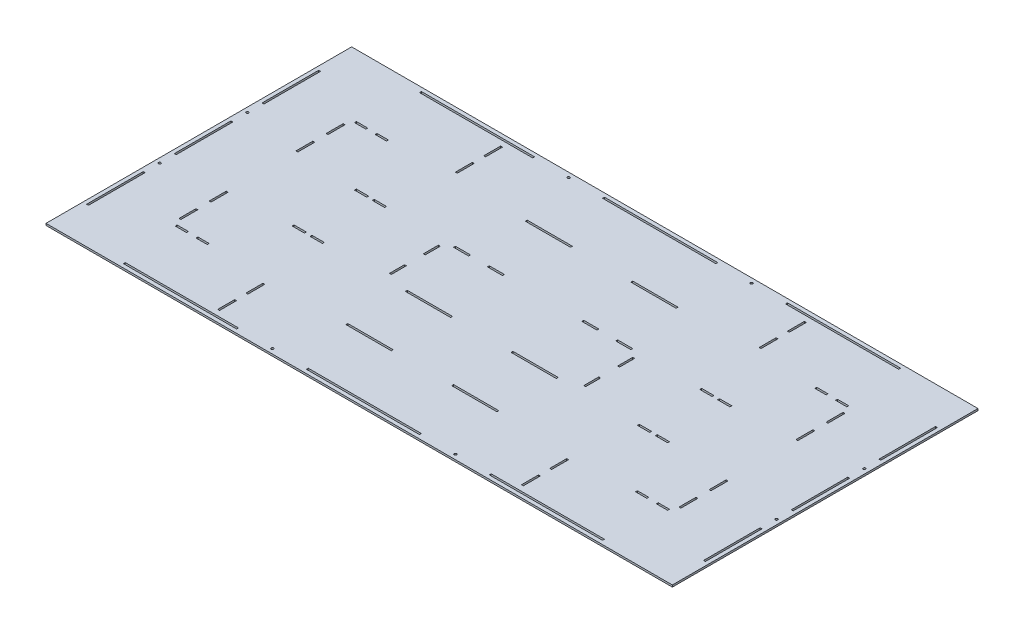
SolidWorks part; units mm, degrees
ref_plane "Alzado" through (0, 0, 0) normal (0, 0, 1) x (1, 0, 0)
ref_plane "Planta" through (0, 0, 0) normal (0, 1, 0) x (1, 0, 0)
ref_plane "Vista lateral" through (0, 0, 0) normal (1, 0, 0) x (0, 0, -1)
sketch "Croquis1" plane through (0, 0, 0) normal (0, 1, 0) x (1, 0, 0)
  line L4 (-447.0447, -95.6027) -> (-447.0447, -240.6027)
  line L5 (-2097.0447, -803.1027) -> (-437.0447, -803.1027)
  line L6 (-437.0447, 6.8973) -> (-437.0447, -803.1027)
  line L7 (-2097.0447, 6.8973) -> (-437.0447, 6.8973)
  line L13 (-2097.0447, 6.8973) -> (-2097.0447, -803.1027)
  line L18 (-2087.0447, -793.1027) -> (-447.0447, -793.1027) construction
  line L19 (-932.0447, -3.1027) -> (-632.0447, -3.1027)
  line L25 (-2097.0447, 6.8973) -> (-2097.0447, -803.1027) construction
  line L29 (-1117.0447, -3.1027) -> (-1417.0447, -3.1027)
  line L30 (-1117.0447, -8.1027) -> (-1117.0447, -3.1027)
  line L32 (-1417.0447, -3.1027) -> (-1417.0447, -8.1027)
  line L33 (-1602.0447, -8.1027) -> (-1902.0447, -8.1027)
  line L34 (-1902.0447, -3.1027) -> (-1602.0447, -3.1027)
  line L35 (-1902.0447, -3.1027) -> (-1902.0447, -8.1027)
  line L36 (-1602.0447, -3.1027) -> (-1602.0447, -8.1027)
  line L37 (-2097.0447, 6.8973) -> (-437.0447, 6.8973)
  line L38 (-632.0447, -3.1027) -> (-632.0447, -8.1027)
  line L39 (-2087.0447, -3.1027) -> (-447.0447, -3.1027) construction
  line L40 (-932.0447, -3.1027) -> (-932.0447, -8.1027)
  line L41 (-452.0447, -95.6027) -> (-452.0447, -90.6027)
  line L42 (-447.0447, -3.1027) -> (-447.0447, -793.1027) construction
  line L45 (-452.0447, -95.6027) -> (-452.0447, -240.6027)
  line L49 (-452.0447, -328.1027) -> (-452.0447, -473.1027)
  line L51 (-447.0447, -328.1027) -> (-447.0447, -473.1027)
  line L53 (-452.0447, -560.6027) -> (-452.0447, -705.6027)
  line L55 (-447.0447, -560.6027) -> (-447.0447, -705.6027)
  line L67 (-2087.0447, -3.1027) -> (-2087.0447, -793.1027) construction
  line L68 (-447.0447, -95.6027) -> (-447.0447, -90.6027)
  line L69 (-447.0447, -90.6027) -> (-452.0447, -90.6027)
  line L70 (-447.0447, -328.1027) -> (-447.0447, -323.1027)
  line L71 (-447.0447, -240.6027) -> (-452.0447, -240.6027) construction
  line L72 (-447.0447, -240.6027) -> (-452.0447, -240.6027)
  line L73 (-452.0447, -328.1027) -> (-452.0447, -323.1027)
  line L74 (-452.0447, -323.1027) -> (-447.0447, -323.1027)
  line L75 (-447.0447, -473.1027) -> (-452.0447, -473.1027)
  line L76 (-452.0447, -560.6027) -> (-452.0447, -555.6027)
  line L77 (-447.0447, -560.6027) -> (-447.0447, -555.6027)
  line L78 (-447.0447, -555.6027) -> (-452.0447, -555.6027)
  line L79 (-632.0447, -8.1027) -> (-932.0447, -8.1027)
  line L80 (-447.0447, -705.6027) -> (-452.0447, -705.6027)
  line L81 (-2087.0447, -240.6027) -> (-2082.0447, -240.6027) construction
  line L82 (-2087.0447, -705.6027) -> (-2082.0447, -705.6027)
  line L83 (-2087.0447, -555.6027) -> (-2082.0447, -555.6027)
  line L84 (-2087.0447, -560.6027) -> (-2087.0447, -555.6027)
  line L85 (-2082.0447, -560.6027) -> (-2082.0447, -555.6027)
  line L86 (-2087.0447, -473.1027) -> (-2082.0447, -473.1027)
  line L87 (-2082.0447, -323.1027) -> (-2087.0447, -323.1027)
  line L88 (-2082.0447, -328.1027) -> (-2082.0447, -323.1027)
  line L89 (-2087.0447, -240.6027) -> (-2082.0447, -240.6027)
  line L90 (-2087.0447, -328.1027) -> (-2087.0447, -323.1027)
  line L91 (-2087.0447, -90.6027) -> (-2082.0447, -90.6027)
  line L92 (-2087.0447, -95.6027) -> (-2087.0447, -90.6027)
  line L93 (-2087.0447, -560.6027) -> (-2087.0447, -705.6027)
  line L94 (-2082.0447, -560.6027) -> (-2082.0447, -705.6027)
  line L95 (-2087.0447, -328.1027) -> (-2087.0447, -473.1027)
  line L96 (-2082.0447, -328.1027) -> (-2082.0447, -473.1027)
  line L97 (-2082.0447, -95.6027) -> (-2082.0447, -240.6027)
  line L98 (-2082.0447, -95.6027) -> (-2082.0447, -90.6027)
  line L99 (-2087.0447, -95.6027) -> (-2087.0447, -240.6027)
  line L100 (-1117.0447, -8.1027) -> (-1417.0447, -8.1027)
  line L101 (-1117.0447, -788.1027) -> (-1417.0447, -788.1027)
  line L102 (-632.0447, -788.1027) -> (-932.0447, -788.1027)
  line L103 (-932.0447, -793.1027) -> (-932.0447, -788.1027)
  line L104 (-632.0447, -793.1027) -> (-632.0447, -788.1027)
  line L105 (-1602.0447, -793.1027) -> (-1602.0447, -788.1027)
  line L106 (-1902.0447, -793.1027) -> (-1902.0447, -788.1027)
  line L107 (-1902.0447, -793.1027) -> (-1602.0447, -793.1027)
  line L108 (-1602.0447, -788.1027) -> (-1902.0447, -788.1027)
  line L109 (-1417.0447, -793.1027) -> (-1417.0447, -788.1027)
  line L110 (-1117.0447, -788.1027) -> (-1117.0447, -793.1027)
  line L111 (-1117.0447, -793.1027) -> (-1417.0447, -793.1027)
  line L112 (-932.0447, -793.1027) -> (-632.0447, -793.1027)
  dimension "D5" = 5
  dimension "D10" = 145
  dimension "D3" = 1660
  dimension "D12" = 5
  dimension "D13" = 145
  dimension "D14" = 5
  dimension "D15" = 5
extrude "Saliente-Extruir3" add sketch "Croquis1" along normal blind 5 contours L7 L13 L5 L6 L112 L103 L102 L104 L108 L105 L107 L106 L99 L92 L91 L98 L97 L89 L34 L36 L33 L35 L4 L72 L45 L41 L69 L68 L51 L75 L49 L73 L74 L70 L38 L79 L40 L19 L55 L80 L53 L76 L78
sketch "Croquis2" plane through (0, 5, 0) normal (0, 1, 0) x (1, 0, 0)
  line L0 (-1007.0447, -463.1027) -> (-1007.0447, -423.1027)
  line L1 (-669.5447, -638.1027) -> (-699.5447, -638.1027)
  line L2 (-1067.0447, -638.1027) -> (-1187.0447, -638.1027)
  line L5 (-1467.0447, -633.1027) -> (-1347.0447, -633.1027)
  line L8 (-1602.0447, -788.1027) -> (-1902.0447, -788.1027) construction
  line L11 (-1672.0447, -788.1027) -> (-1667.0447, -788.1027)
  line L19 (-644.5447, -633.1027) -> (-644.5447, -638.1027)
  line L24 (-1464.5447, -483.1027) -> (-1344.5447, -483.1027)
  line L25 (-669.5447, -638.1027) -> (-669.5447, -633.1027)
  line L26 (-1672.0447, -8.1027) -> (-1667.0447, -8.1027)
  line L61 (-769.5447, -478.1027) -> (-802.0447, -478.1027)
  line L63 (-849.5447, -483.1027) -> (-817.0447, -483.1027)
  line L65 (-602.0447, -490.6027) -> (-602.0447, -535.6027)
  line L68 (-699.5447, -633.1027) -> (-669.5447, -633.1027)
  line L70 (-862.0447, -653.1027) -> (-862.0447, -698.1027)
  line L72 (-867.0447, -653.1027) -> (-867.0447, -698.1027)
  line L74 (-1032.0447, -313.1027) -> (-1072.0447, -313.1027)
  line L76 (-1162.0447, -318.1027) -> (-1122.0447, -318.1027)
  line L77 (-1012.0447, -333.1027) -> (-1012.0447, -373.1027)
  line L78 (-1064.5447, -478.1027) -> (-1184.5447, -478.1027)
  line L80 (-1122.0447, -313.1027) -> (-1122.0447, -318.1027)
  line L87 (-699.5447, -633.1027) -> (-699.5447, -638.1027)
  line L88 (-614.5447, -638.1027) -> (-644.5447, -638.1027)
  line L89 (-614.5447, -638.1027) -> (-614.5447, -633.1027)
  line L90 (-607.0447, -615.6027) -> (-602.0447, -615.6027)
  line L91 (-607.0447, -570.6027) -> (-602.0447, -570.6027)
  line L92 (-602.0447, -570.6027) -> (-602.0447, -615.6027)
  line L93 (-607.0447, -490.6027) -> (-607.0447, -535.6027)
  line L94 (-1187.0447, -158.1027) -> (-1187.0447, -163.1027)
  line L95 (-607.0447, -535.6027) -> (-602.0447, -535.6027)
  line L96 (-607.0447, -615.6027) -> (-607.0447, -570.6027)
  line L97 (-802.0447, -478.1027) -> (-802.0447, -483.1027)
  line L99 (-604.5447, -535.6027) -> (-602.0447, -535.6027) construction
  line L100 (-817.0447, -483.1027) -> (-817.0447, -478.1027)
  line L101 (-644.5447, -633.1027) -> (-614.5447, -633.1027)
  line L102 (-1467.0447, -158.1027) -> (-1467.0447, -163.1027)
  line L103 (-867.0447, -653.1027) -> (-862.0447, -653.1027)
  line L104 (-867.0447, -698.1027) -> (-862.0447, -698.1027)
  line L105 (-862.0447, -728.1027) -> (-867.0447, -728.1027)
  line L106 (-862.0447, -728.1027) -> (-862.0447, -773.1027)
  line L107 (-867.0447, -728.1027) -> (-867.0447, -773.1027)
  line L108 (-867.0447, -773.1027) -> (-862.0447, -773.1027)
  line L109 (-1347.0447, -638.1027) -> (-1467.0447, -638.1027)
  line L110 (-849.5447, -478.1027) -> (-849.5447, -483.1027)
  line L111 (-769.5447, -483.1027) -> (-769.5447, -478.1027)
  line L112 (-802.0447, -483.1027) -> (-769.5447, -483.1027)
  line L113 (-817.0447, -478.1027) -> (-849.5447, -478.1027)
  line L114 (-1267.0447, -8.1027) -> (-1267.0447, -98.1027)
  line L115 (-1064.5447, -478.1027) -> (-1064.5447, -483.1027)
  line L116 (-1184.5447, -478.1027) -> (-1184.5447, -483.1027)
  line L117 (-1464.5447, -478.1027) -> (-1464.5447, -483.1027)
  line L118 (-1344.5447, -478.1027) -> (-1344.5447, -483.1027)
  line L121 (-1184.5447, -483.1027) -> (-1064.5447, -483.1027)
  line L122 (-1344.5447, -478.1027) -> (-1464.5447, -478.1027)
  line L123 (-1117.0447, -8.1027) -> (-1417.0447, -8.1027) construction
  line L124 (-1412.0447, -313.1027) -> (-1412.0447, -318.1027) construction
  line L126 (-1067.0447, -633.1027) -> (-1067.0447, -638.1027)
  line L127 (-1187.0447, -638.1027) -> (-1187.0447, -633.1027)
  line L128 (-1347.0447, -638.1027) -> (-1347.0447, -633.1027)
  line L129 (-1467.0447, -633.1027) -> (-1467.0447, -638.1027)
  line L130 (-1187.0447, -633.1027) -> (-1067.0447, -633.1027)
  line L131 (-1412.0447, -313.1027) -> (-1372.0447, -313.1027)
  line L132 (-1927.0447, -305.6027) -> (-1932.0447, -305.6027)
  line L133 (-1462.0447, -318.1027) -> (-1502.0447, -318.1027)
  line L134 (-1012.0447, -423.1027) -> (-1012.0447, -463.1027)
  line L136 (-1012.0447, -463.1027) -> (-1007.0447, -463.1027)
  line L137 (-1012.0447, -423.1027) -> (-1007.0447, -423.1027)
  line L138 (-1012.0447, -373.1027) -> (-1007.0447, -373.1027)
  line L139 (-1007.0447, -333.1027) -> (-1012.0447, -333.1027)
  line L140 (-1007.0447, -373.1027) -> (-1007.0447, -333.1027)
  line L141 (-1032.0447, -313.1027) -> (-1032.0447, -318.1027)
  line L142 (-1072.0447, -313.1027) -> (-1072.0447, -318.1027)
  line L143 (-1372.0447, -313.1027) -> (-1372.0447, -318.1027)
  line L144 (-1162.0447, -313.1027) -> (-1162.0447, -318.1027)
  line L145 (-1122.0447, -313.1027) -> (-1122.0447, -318.1027) construction
  line L146 (-1072.0447, -318.1027) -> (-1032.0447, -318.1027)
  line L147 (-1122.0447, -313.1027) -> (-1162.0447, -313.1027)
  line L148 (-1929.5447, -535.6027) -> (-1932.0447, -535.6027) construction
  line L149 (-1717.0447, -478.1027) -> (-1684.5447, -478.1027)
  line L150 (-1732.0447, -483.1027) -> (-1764.5447, -483.1027)
  line L151 (-1764.5447, -483.1027) -> (-1764.5447, -478.1027)
  line L152 (-1684.5447, -478.1027) -> (-1684.5447, -483.1027)
  line L153 (-1717.0447, -483.1027) -> (-1717.0447, -478.1027)
  line L154 (-1732.0447, -478.1027) -> (-1732.0447, -483.1027)
  line L155 (-1927.0447, -535.6027) -> (-1932.0447, -535.6027)
  line L156 (-1462.0447, -313.1027) -> (-1462.0447, -318.1027)
  line L157 (-1927.0447, -490.6027) -> (-1927.0447, -535.6027)
  line L159 (-1932.0447, -490.6027) -> (-1932.0447, -535.6027)
  line L160 (-1684.5447, -483.1027) -> (-1717.0447, -483.1027)
  line L161 (-1764.5447, -478.1027) -> (-1732.0447, -478.1027)
  line L162 (-1667.0447, -773.1027) -> (-1672.0447, -773.1027)
  line L163 (-1467.0447, -158.1027) -> (-1347.0447, -158.1027)
  line L164 (-1067.0447, -163.1027) -> (-1187.0447, -163.1027)
  line L165 (-1502.0447, -313.1027) -> (-1502.0447, -318.1027)
  line L166 (-1527.0447, -373.1027) -> (-1527.0447, -333.1027)
  line L167 (-1527.0447, -333.1027) -> (-1522.0447, -333.1027)
  line L168 (-1522.0447, -373.1027) -> (-1527.0447, -373.1027)
  line L169 (-1522.0447, -423.1027) -> (-1527.0447, -423.1027)
  line L170 (-1522.0447, -423.1027) -> (-1522.0447, -463.1027)
  line L171 (-1667.0447, -728.1027) -> (-1667.0447, -773.1027)
  line L172 (-1672.0447, -728.1027) -> (-1672.0447, -773.1027)
  line L173 (-1672.0447, -728.1027) -> (-1667.0447, -728.1027)
  line L174 (-1667.0447, -698.1027) -> (-1672.0447, -698.1027)
  line L175 (-1667.0447, -653.1027) -> (-1672.0447, -653.1027)
  line L176 (-1889.5447, -633.1027) -> (-1919.5447, -633.1027)
  line L177 (-1927.0447, -615.6027) -> (-1927.0447, -570.6027)
  line L178 (-1932.0447, -570.6027) -> (-1932.0447, -615.6027)
  line L179 (-1927.0447, -570.6027) -> (-1932.0447, -570.6027)
  line L180 (-1927.0447, -615.6027) -> (-1932.0447, -615.6027)
  line L181 (-1919.5447, -638.1027) -> (-1919.5447, -633.1027)
  line L182 (-1919.5447, -638.1027) -> (-1889.5447, -638.1027)
  line L183 (-1834.5447, -633.1027) -> (-1834.5447, -638.1027)
  line L184 (-1667.0447, -653.1027) -> (-1667.0447, -698.1027)
  line L185 (-1672.0447, -653.1027) -> (-1672.0447, -698.1027)
  line L186 (-1834.5447, -633.1027) -> (-1864.5447, -633.1027)
  line L187 (-1864.5447, -638.1027) -> (-1864.5447, -633.1027)
  line L188 (-1889.5447, -633.1027) -> (-1889.5447, -638.1027)
  line L189 (-1412.0447, -313.1027) -> (-1412.0447, -318.1027)
  line L190 (-1522.0447, -333.1027) -> (-1522.0447, -373.1027)
  line L191 (-1864.5447, -638.1027) -> (-1834.5447, -638.1027)
  line L192 (-1187.0447, -158.1027) -> (-1067.0447, -158.1027)
  line L193 (-1372.0447, -318.1027) -> (-1412.0447, -318.1027)
  line L194 (-1347.0447, -158.1027) -> (-1347.0447, -163.1027)
  line L195 (-1502.0447, -313.1027) -> (-1462.0447, -313.1027)
  line L196 (-1067.0447, -163.1027) -> (-1067.0447, -158.1027)
  line L197 (-1347.0447, -163.1027) -> (-1467.0447, -163.1027)
  line L198 (-1527.0447, -463.1027) -> (-1527.0447, -423.1027)
  line L199 (-1522.0447, -463.1027) -> (-1527.0447, -463.1027)
  line L200 (-1927.0447, -490.6027) -> (-1932.0447, -490.6027)
  line L201 (-602.0447, -490.6027) -> (-607.0447, -490.6027)
  line L202 (-602.0447, -305.6027) -> (-607.0447, -305.6027)
  line L206 (-604.5447, -260.6027) -> (-602.0447, -260.6027) construction
  line L207 (-817.0447, -318.1027) -> (-849.5447, -318.1027)
  line L208 (-802.0447, -313.1027) -> (-769.5447, -313.1027)
  line L209 (-769.5447, -313.1027) -> (-769.5447, -318.1027)
  line L210 (-849.5447, -318.1027) -> (-849.5447, -313.1027)
  line L211 (-867.0447, -23.1027) -> (-862.0447, -23.1027)
  line L212 (-867.0447, -68.1027) -> (-867.0447, -23.1027)
  line L213 (-862.0447, -68.1027) -> (-862.0447, -23.1027)
  line L214 (-862.0447, -68.1027) -> (-867.0447, -68.1027)
  line L215 (-867.0447, -98.1027) -> (-862.0447, -98.1027)
  line L216 (-867.0447, -143.1027) -> (-862.0447, -143.1027)
  line L217 (-644.5447, -163.1027) -> (-614.5447, -163.1027)
  line L218 (-817.0447, -313.1027) -> (-817.0447, -318.1027)
  line L219 (-802.0447, -318.1027) -> (-802.0447, -313.1027)
  line L220 (-607.0447, -180.6027) -> (-607.0447, -225.6027)
  line L221 (-607.0447, -260.6027) -> (-602.0447, -260.6027)
  line L223 (-607.0447, -305.6027) -> (-607.0447, -260.6027)
  line L224 (-602.0447, -225.6027) -> (-602.0447, -180.6027)
  line L225 (-607.0447, -225.6027) -> (-602.0447, -225.6027)
  line L226 (-607.0447, -180.6027) -> (-602.0447, -180.6027)
  line L227 (-614.5447, -158.1027) -> (-614.5447, -163.1027)
  line L228 (-614.5447, -158.1027) -> (-644.5447, -158.1027)
  line L229 (-699.5447, -163.1027) -> (-699.5447, -158.1027)
  line L230 (-867.0447, -143.1027) -> (-867.0447, -98.1027)
  line L231 (-862.0447, -143.1027) -> (-862.0447, -98.1027)
  line L232 (-699.5447, -163.1027) -> (-669.5447, -163.1027)
  line L234 (-602.0447, -305.6027) -> (-602.0447, -260.6027)
  line L235 (-849.5447, -313.1027) -> (-817.0447, -313.1027)
  line L236 (-769.5447, -318.1027) -> (-802.0447, -318.1027)
  line L237 (-669.5447, -158.1027) -> (-669.5447, -163.1027)
  line L238 (-644.5447, -163.1027) -> (-644.5447, -158.1027)
  line L239 (-669.5447, -158.1027) -> (-699.5447, -158.1027)
  line L240 (-1929.5447, -260.6027) -> (-1932.0447, -260.6027) construction
  line L241 (-1864.5447, -158.1027) -> (-1834.5447, -158.1027)
  line L242 (-1889.5447, -163.1027) -> (-1889.5447, -158.1027)
  line L243 (-1864.5447, -158.1027) -> (-1864.5447, -163.1027)
  line L244 (-1834.5447, -163.1027) -> (-1864.5447, -163.1027)
  line L245 (-1672.0447, -143.1027) -> (-1672.0447, -98.1027)
  line L246 (-1667.0447, -143.1027) -> (-1667.0447, -98.1027)
  line L247 (-1834.5447, -163.1027) -> (-1834.5447, -158.1027)
  line L248 (-1919.5447, -158.1027) -> (-1889.5447, -158.1027)
  line L249 (-1919.5447, -158.1027) -> (-1919.5447, -163.1027)
  line L250 (-1927.0447, -180.6027) -> (-1932.0447, -180.6027)
  line L251 (-1927.0447, -225.6027) -> (-1932.0447, -225.6027)
  line L252 (-1932.0447, -225.6027) -> (-1932.0447, -180.6027)
  line L253 (-1927.0447, -180.6027) -> (-1927.0447, -225.6027)
  line L254 (-1889.5447, -163.1027) -> (-1919.5447, -163.1027)
  line L255 (-1667.0447, -143.1027) -> (-1672.0447, -143.1027)
  line L256 (-1667.0447, -98.1027) -> (-1672.0447, -98.1027)
  line L257 (-1672.0447, -68.1027) -> (-1667.0447, -68.1027)
  line L258 (-1672.0447, -68.1027) -> (-1672.0447, -23.1027)
  line L259 (-1667.0447, -68.1027) -> (-1667.0447, -23.1027)
  line L260 (-1667.0447, -23.1027) -> (-1672.0447, -23.1027)
  line L261 (-1764.5447, -318.1027) -> (-1732.0447, -318.1027)
  line L262 (-1684.5447, -313.1027) -> (-1717.0447, -313.1027)
  line L263 (-1932.0447, -305.6027) -> (-1932.0447, -260.6027)
  line L265 (-1927.0447, -305.6027) -> (-1927.0447, -260.6027)
  line L267 (-1927.0447, -260.6027) -> (-1932.0447, -260.6027)
  line L268 (-1732.0447, -318.1027) -> (-1732.0447, -313.1027)
  line L269 (-1717.0447, -313.1027) -> (-1717.0447, -318.1027)
  line L270 (-1684.5447, -318.1027) -> (-1684.5447, -313.1027)
  line L271 (-1764.5447, -313.1027) -> (-1764.5447, -318.1027)
  line L272 (-1732.0447, -313.1027) -> (-1764.5447, -313.1027)
  line L273 (-1717.0447, -318.1027) -> (-1684.5447, -318.1027)
  dimension "D1" = 120
extrude "Cortar-Extruir2" cut sketch "Croquis2" against normal blind 10 contours L226 L220 L225 L224 | L238 L217 L227 L228 | L214 L213 L211 L212 | L216 L231 L215 L230 | L236 L209 L208 L219 | L235 L210 L207 L218 | L93 L95 L65 L202 | L96 L90 L92 L91 | L97 L112 L111 L61 | L100 L113 L110 L63 | L107 L108 L106 L105 | L175 L185 L174 L184 | L173 L172 L162 L171 | L187 L191 L183 L186 | L259 L260 L258 L257 | L246 L256 L245 L255 | L232 L237 L239 L229 | L101 L89 L88 L19 | L68 L25 L1 L87 | L70 L104 L72 L103 | L134 L136 L0 L137 | L78 L116 L121 L115 | L77 L138 L140 L139 | L74 L142 L146 L141 | L76 L80 L147 L144 | L164 L94 L192 L196 | L130 L126 L2 L127 | L24 L118 L122 L117 | L163 L194 L197 L102 | L5 L128 L109 L129 | L176 L181 L182 L188 | L177 L179 L178 L180 | L159 L155 L157 L200 | L263 L267 L265 L132 | L252 L250 L253 L251 | L248 L242 L254 L249 | L241 L247 L244 L243 | L262 L269 L273 L270 | L149 L152 L160 L153 | L150 L151 L161 L154 | L261 L268 L272 L271 | L166 L167 L190 L168 | L169 L198 L199 L170 | L133 L165 L195 L156 | L131 L143 L193 L189
sketch "Croquis3" plane through (0, 5, 0) normal (0, 1, 0) x (1, 0, 0)
  line L0 (-2084.5447, -240.6027) -> (-2084.5447, -323.1027) construction
  line L1 (-2087.0447, -240.6027) -> (-2082.0447, -240.6027) construction
  line L2 (-2082.0447, -323.1027) -> (-2087.0447, -323.1027) construction
  line L3 (-2084.5447, -473.1027) -> (-2084.5447, -555.6027) construction
  line L4 (-2087.0447, -473.1027) -> (-2082.0447, -473.1027) construction
  line L5 (-2087.0447, -555.6027) -> (-2082.0447, -555.6027) construction
  line L6 (-1602.0447, -790.6027) -> (-1417.0447, -790.6027) construction
  line L7 (-1602.0447, -793.1027) -> (-1602.0447, -788.1027) construction
  line L8 (-1417.0447, -793.1027) -> (-1417.0447, -788.1027) construction
  line L9 (-932.0447, -790.6027) -> (-1117.0447, -790.6027) construction
  line L10 (-932.0447, -793.1027) -> (-932.0447, -788.1027) construction
  line L11 (-1117.0447, -788.1027) -> (-1117.0447, -793.1027) construction
  line L12 (-449.5447, -473.1027) -> (-449.5447, -555.6027) construction
  line L13 (-447.0447, -473.1027) -> (-452.0447, -473.1027) construction
  line L14 (-447.0447, -555.6027) -> (-452.0447, -555.6027) construction
  line L15 (-449.5447, -240.6027) -> (-449.5447, -323.1027) construction
  line L16 (-447.0447, -240.6027) -> (-452.0447, -240.6027) construction
  line L17 (-452.0447, -323.1027) -> (-447.0447, -323.1027) construction
  line L18 (-1117.0447, -8.1027) -> (-1117.0447, -3.1027) construction
  line L19 (-932.0447, -5.6027) -> (-1117.0447, -5.6027) construction
  line L20 (-932.0447, -3.1027) -> (-932.0447, -8.1027) construction
  line L21 (-1417.0447, -5.6027) -> (-1602.0447, -5.6027) construction
  line L22 (-1417.0447, -3.1027) -> (-1417.0447, -8.1027) construction
  line L23 (-1602.0447, -3.1027) -> (-1602.0447, -8.1027) construction
  circle A0 centre (-2084.5447, -281.8527) radius 3.2
  circle A1 centre (-2084.5447, -514.3527) radius 3.2
  circle A2 centre (-1509.5447, -790.6027) radius 3.2
  circle A3 centre (-1024.5447, -790.6027) radius 3.2
  circle A4 centre (-449.5447, -514.3527) radius 3.2
  circle A5 centre (-449.5447, -281.8527) radius 3.2
  circle A6 centre (-1024.5447, -5.6027) radius 3.2
  circle A7 centre (-1509.5447, -5.6027) radius 3.2
extrude "Cortar-Extruir3" cut sketch "Croquis3" against normal blind 10
